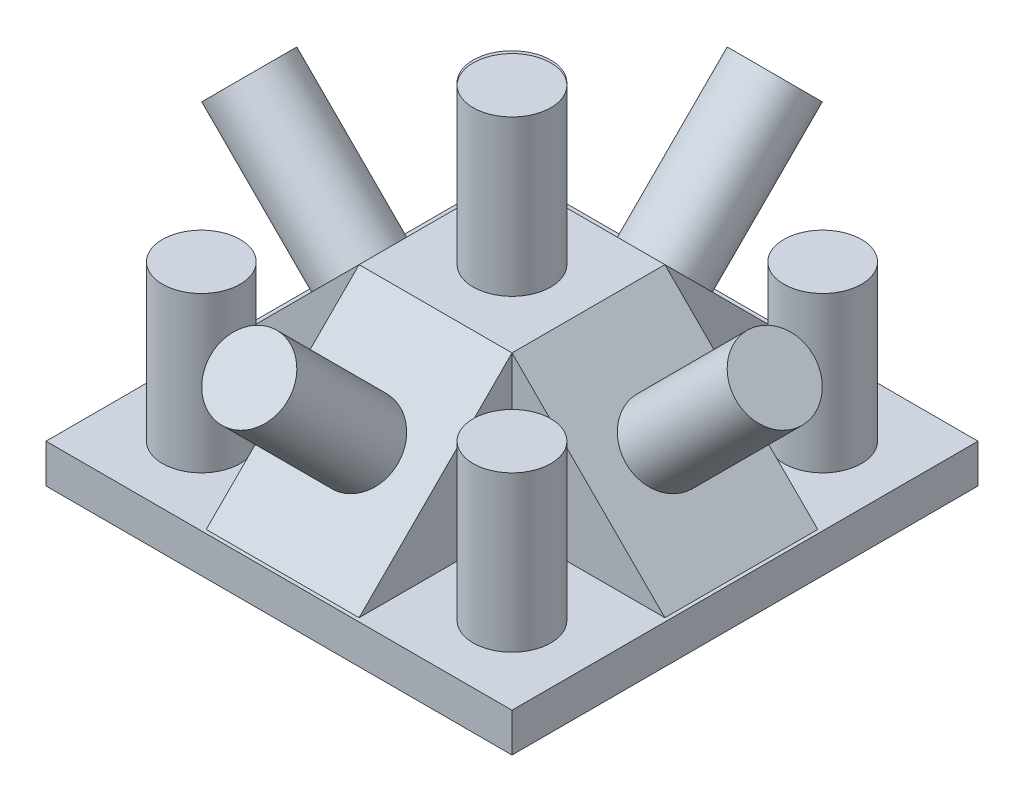
SolidWorks part; units mm, degrees
ref_plane "Front Plane" through (0, 0, 0) normal (0, 0, 1) x (1, 0, 0)
ref_plane "Top Plane" through (0, 0, 0) normal (0, 1, 0) x (1, 0, 0)
ref_plane "Right Plane" through (0, 0, 0) normal (1, 0, 0) x (0, 0, -1)
sketch "Sketch1" plane through (0, 0, 0) normal (0, 1, 0) x (1, 0, 0)
  line L0 (50.8, 152.4) -> (50.8, 101.6) construction
  line L1 (0, 152.4) -> (152.4, 152.4)
  line L2 (0, 152.4) -> (0, 0)
  line L3 (0, 0) -> (152.4, 0)
  line L4 (152.4, 152.4) -> (152.4, 0)
  line L5 (50.8, 101.6) -> (50.8, 50.8) construction
  line L6 (50.8, 50.8) -> (50.8, 0) construction
  line L7 (101.6, 152.4) -> (101.6, 101.6) construction
  line L8 (101.6, 101.6) -> (101.6, 50.8) construction
  line L9 (101.6, 50.8) -> (101.6, 0) construction
  line L10 (0, 101.6) -> (50.8, 101.6) construction
  line L11 (50.8, 101.6) -> (101.6, 101.6) construction
  line L12 (101.6, 101.6) -> (152.4, 101.6) construction
  line L13 (0, 50.8) -> (50.8, 50.8) construction
  line L14 (50.8, 50.8) -> (101.6, 50.8) construction
  line L15 (101.6, 50.8) -> (152.4, 50.8) construction
  dimension "D1" = 152.4
extrude "Boss-Extrude1" add sketch "Sketch1" against normal blind 12.7
sketch "Sketch2" plane through (0, 0, 0) normal (0, 1, 0) x (1, 0, 0)
  line L0 (50.8, 152.4) -> (0, 101.6) construction
  line L1 (101.6, 152.4) -> (152.4, 101.6) construction
  line L2 (152.4, 50.8) -> (101.6, 0) construction
  line L3 (0, 50.8) -> (50.8, 0) construction
  circle A0 centre (25.4, 127) radius 12.7
  circle A1 centre (127, 127) radius 12.7
  circle A2 centre (127, 25.4) radius 12.7
  circle A3 centre (25.4, 25.4) radius 12.7
  dimension "D1" = 25.4
extrude "Boss-Extrude2" add sketch "Sketch2" along normal blind 50.8
sketch "Sketch3" plane through (0, 0, 0) normal (0, 1, 0) x (1, 0, 0)
  line L0 (51.2, 151.2) -> (51.2, 101.2)
  line L1 (51.2, 101.2) -> (1.2, 101.2)
  line L2 (1.2, 101.2) -> (1.2, 51.2)
  line L3 (1.2, 51.2) -> (51.2, 51.2)
  line L4 (51.2, 51.2) -> (51.2, 1.2)
  line L5 (51.2, 1.2) -> (101.2, 1.2)
  line L6 (101.2, 1.2) -> (101.2, 51.2)
  line L7 (101.2, 51.2) -> (151.2, 51.2)
  line L8 (151.2, 51.2) -> (151.2, 101.2)
  line L9 (151.2, 101.2) -> (101.2, 101.2)
  line L10 (101.2, 101.2) -> (101.2, 151.2)
  line L11 (101.2, 151.2) -> (51.2, 151.2)
  line L12 (50.8, 101.6) -> (101.6, 101.6) construction
  line L13 (50.8, 101.6) -> (50.8, 50.8) construction
  line L14 (0, 76.2) -> (152.4, 76.2) construction
  line L15 (0, 152.4) -> (0, 0) construction
  line L16 (152.4, 152.4) -> (152.4, 0) construction
  line L17 (76.2, 151.2) -> (76.2, 1.2) construction
  point P24 (76.2, 76.2)
  point P25 (0, 0)
  dimension "D1" = 50
extrude "Boss-Extrude3" add sketch "Sketch3" along normal blind 50
sketch "Sketch4" plane through (0, 0, -51.2) normal (0, 0, 1) x (1, 0, 0)
  line L0 (1.2, 0) -> (51.2, 50)
  line L1 (51.2, 50) -> (1.2, 50)
  line L2 (1.2, 50) -> (1.2, 0)
  line L3 (1.2, 50) -> (1.2, 0) construction
  line L4 (1.2, 50) -> (51.2, 50) construction
  line L5 (101.2, 50) -> (151.2, 0)
  line L6 (151.2, 0) -> (151.2, 50)
  line L7 (151.2, 50) -> (101.2, 50)
  line L8 (101.2, 50) -> (151.2, 50) construction
  line L9 (151.2, 50) -> (151.2, 0) construction
extrude "Cut-Extrude1" cut sketch "Sketch4" against normal up to surface (50 mm away) up to face at (26.2, 25, -101.2)
sketch "Sketch5" plane through (101.2, 0, 0) normal (1, 0, 0) x (0, 0, -1)
  line L0 (1.2, 0) -> (51.2, 50)
  line L1 (51.2, 50) -> (1.2, 50)
  line L2 (1.2, 50) -> (1.2, 0)
  line L3 (101.2, 50) -> (151.2, 0)
  line L4 (151.2, 0) -> (151.2, 50)
  line L5 (151.2, 50) -> (101.2, 50)
  line L6 (1.2, 50) -> (1.2, 0) construction
  line L7 (1.2, 50) -> (51.2, 50) construction
  line L8 (101.2, 50) -> (151.2, 50) construction
  line L9 (151.2, 50) -> (151.2, 0) construction
extrude "Cut-Extrude2" cut sketch "Sketch5" against normal up to surface (50 mm away) up to face at (51.2, 25, -26.2)
sketch "Sketch6" plane through (75.6, 75.6, 0) normal (0.7071, 0.7071, 0) x (0, 0, -1)
  line L0 (51.2, -71.5592) -> (101.2, -71.5592) construction
  line L1 (51.2, -36.2039) -> (51.2, -106.9145) construction
  line L2 (101.2, -106.9145) -> (101.2, -36.2039) construction
  circle A0 centre (76.2, -71.5592) radius 12.7
  dimension "D1" = 25.4
extrude "Boss-Extrude4" add sketch "Sketch6" along normal blind 50.8
sketch "Sketch7" plane through (0, 75.6, -75.6) normal (0, 0.7071, -0.7071) x (1, 0, 0)
  line L0 (101.2, 71.5592) -> (51.2, 71.5592) construction
  line L1 (101.2, 36.2039) -> (101.2, 106.9145) construction
  line L2 (51.2, 106.9145) -> (51.2, 36.2039) construction
  circle A0 centre (76.2, 71.5592) radius 12.7
  dimension "D1" = 25.4
extrude "Boss-Extrude5" add sketch "Sketch7" along normal blind 50.8
sketch "Sketch8" plane through (0.6, -0.6, 0) normal (-0.7071, 0.7071, 0) x (0, 0, 1)
  line L0 (-101.2, 36.2039) -> (-51.2, 36.2039) construction
  line L1 (-101.2, 71.5592) -> (-101.2, 0.8485) construction
  line L2 (-51.2, 0.8485) -> (-51.2, 71.5592) construction
  circle A0 centre (-76.2, 36.2039) radius 12.7
  dimension "D1" = 25.4
extrude "Boss-Extrude6" add sketch "Sketch8" along normal blind 50.8
sketch "Sketch9" plane through (0, -0.6, -0.6) normal (0, 0.7071, 0.7071) x (1, 0, 0)
  line L0 (51.2, 36.2039) -> (101.2, 36.2039) construction
  line L1 (51.2, 71.5592) -> (51.2, 0.8485) construction
  line L2 (101.2, 0.8485) -> (101.2, 71.5592) construction
  circle A0 centre (76.2, 36.2039) radius 12.7
  dimension "D1" = 25.4
extrude "Boss-Extrude7" add sketch "Sketch9" along normal blind 50.8
sketch "Sketch10" plane through (0, 50, 0) normal (0, 1, 0) x (1, 0, 0)
  line L0 (51.2, 76.2) -> (101.2, 76.2) construction
  line L1 (51.2, 101.2) -> (51.2, 51.2) construction
  line L2 (101.2, 101.2) -> (101.2, 51.2) construction
  circle A0 centre (76.2, 76.2) radius 12.7
  dimension "D1" = 25.4
extrude "Boss-Extrude8" add sketch "Sketch10" along normal blind 50.8
